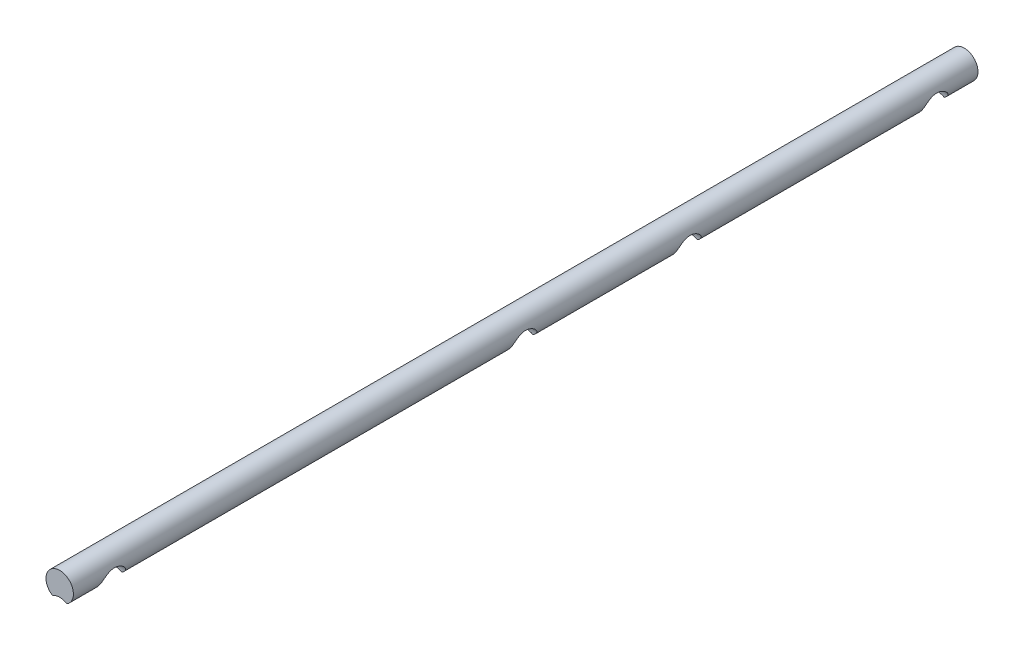
SolidWorks part; units mm, degrees
ref_plane "Спереди" through (0, 0, 0) normal (0, 0, 1) x (1, 0, 0)
ref_plane "Сверху" through (0, 0, 0) normal (0, 1, 0) x (1, 0, 0)
ref_plane "Справа" through (0, 0, 0) normal (1, 0, 0) x (0, 0, -1)
sketch "Эскиз1" plane through (0, 0, 0) normal (0, 0, 1) x (1, 0, 0)
  line L0 (0, 100) -> (0, -70) construction
  circle A0 centre (0, 0) radius 100
  circle A2 centre (0, -175) radius 105
  point P6 (0, 0)
  dimension "D1" = 200
  dimension "D3" = 210
  dimension "D2" = 170
extrude "Бобышка-Вытянуть1" add sketch "Эскиз1" along normal mid plane 6600 contours L0 A0 A2 | A0 L0 A2
sketch "Эскиз2" plane through (0, 0, 0) normal (1, 0, 0) x (0, 0, -1)
  line L0 (-3300, 100) -> (-3300, -84.5714) construction
  line L1 (-3300, -84.5714) -> (3300, -84.5714) construction
  line L2 (0, 0) -> (0, 114.413) construction
  circle A0 centre (-3000, -84.5714) radius 100
  circle A1 centre (3000, -84.5714) radius 100
  circle A2 centre (0, -84.5714) radius 100
  circle A3 centre (1200, -84.5714) radius 100
  dimension "D2" = 200
  dimension "D1" = 300
  dimension "D3" = 3000
  dimension "D4" = 1800
extrude "Вырез-Вытянуть1" cut sketch "Эскиз2" against normal mid plane 6000
sketch "Эскиз3" plane through (0, 0, 0) normal (0, 1, 0) x (1, 0, 0)
  line L0 (-100, -3300) -> (100, -3300) construction
  line L1 (0, -2920.923) -> (0, -3079.077) construction
  line L2 (-79.077, -3000) -> (79.077, -3000) construction
  line L3 (0, 0) -> (163.9977, 0) construction
  line L4 (-79.077, 3000) -> (79.077, 3000) construction
  line L5 (0, 2920.923) -> (0, 3079.077) construction
  line L6 (0, 79.077) -> (0, -79.077) construction
  line L7 (79.077, 0) -> (-79.077, 0) construction
  line L8 (-79.077, 1200) -> (79.077, 1200) construction
  line L9 (0, 1120.923) -> (0, 1279.077) construction
  circle A0 centre (0, -3000) radius 79.077 construction
  circle A1 centre (0, 3000) radius 79.077 construction
  circle A2 centre (0, 0) radius 79.077 construction
  circle A3 centre (0, 1200) radius 79.077 construction
  dimension "D2" = 158.1541
  dimension "D1" = 300
  dimension "D3" = 3000
  dimension "D4" = 1800
equation "\"Длина\"= 6000 + 600"
equation "\"D1@Бобышка-Вытянуть1\"=\"Длина\""
